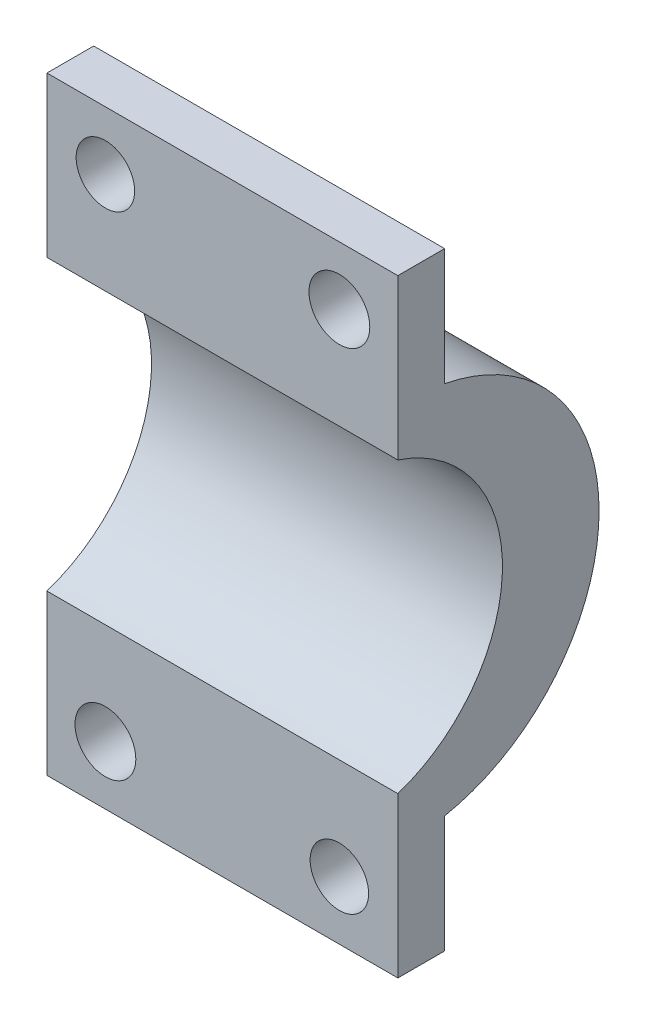
SolidWorks part; units mm, degrees
material "ABS"
ref_plane "Спереди" through (0, 0, 0) normal (0, 0, 1) x (1, 0, 0)
ref_plane "Сверху" through (0, 0, 0) normal (0, 1, 0) x (1, 0, 0)
ref_plane "Справа" through (0, 0, 0) normal (1, 0, 0) x (0, 0, -1)
sketch "Эскиз1" plane through (0, 0, 0) normal (0, 0, 1) x (1, 0, 0)
  line L0 (0, 0) -> (30, 0)
  line L1 (30, 0) -> (30, 32)
  line L2 (30, 32) -> (0, 32)
  line L3 (0, 32) -> (0, 0)
  dimension "D1" = 30
  dimension "D2" = 32
extrude "Бобышка-Вытянуть1" add sketch "Эскиз1" along normal blind 7
ref_plane "Плоскость5" through (0, 0, 0) normal (-1, 0, 0) x (0, 0, 1)
sketch "Эскиз2" plane through (0, 0, 0) normal (-1, 0, 0) x (0, 0, 1)
  line L0 (7, 32) -> (17.9408, 32)
  line L1 (17.9408, 0) -> (7, 0)
  line L2 (7, 0) -> (7, 32)
  line L3 (17.9408, 32) -> (17.9408, 28.35)
  line L4 (17.9408, 3.65) -> (17.9408, 0)
  arc A2 (17.9408, 28.35) -> (17.9408, 3.65) centre (22, 16) ccw
  dimension "D1" = 13
  dimension "D3" = 3.65
  dimension "D2" = 16
  dimension "D4" = 3.65
  dimension "D5" = 15
extrude "Бобышка-Вытянуть2" add sketch "Эскиз2" against normal blind 30
sketch "Эскиз3" plane through (0, 0, 17.9408) normal (0, 0, -1) x (-1, 0, 0)
  line L0 (-30, 16) -> (-30, -10)
  line L1 (-30, 0) -> (-30, 32) construction
  line L2 (-30, -10) -> (0, -10)
  line L3 (0, -10) -> (0, 42)
  line L4 (0, -13.695) -> (0, 13.695) construction
  line L5 (0, 42) -> (-30, 42)
  line L6 (-30, 42) -> (-30, 16)
  line L7 (-30, 37) -> (0, 37) construction
  line L8 (-30, -5) -> (0, -5) construction
  line L9 (-30, 32) -> (0, 32)
  line L10 (-30, 0) -> (0, 0)
  line L11 (0, 32) -> (0, 42)
  line L12 (-30, 42) -> (-30, 32)
  line L13 (-30, 0) -> (-30, -10)
  line L14 (0, -10) -> (0, 0)
  circle A0 centre (-25, 37) radius 2.6
  circle A1 centre (-5, 37) radius 2.5
  circle A2 centre (-5, -5) radius 2.6
  circle A3 centre (-25, -5) radius 2.5
  point P16 (-25, 37)
  point P17 (-5, 37)
  point P18 (-5, -5)
  point P19 (-25, -5)
  line M20 (-30, 32) -> (0, 32)
  dimension "D7" = 5.2
  dimension "D9" = 5
  dimension "D10" = 5
  dimension "D12" = 5.2
  dimension "D13" = 5
  dimension "D1" = 10
  dimension "D2" = 10
  dimension "D3" = 30
  dimension "D4" = 5
  dimension "D5" = 5
  dimension "D6" = 5
  dimension "D8" = 5
  dimension "D11" = 5
extrude "Бобышка-Вытянуть3" add sketch "Эскиз3" along normal blind 4 contours L6 L5 L3 A0 A1 M20 | L0 L10 L3 L2 A2 A3
sketch "Эскиз4" plane through (30, 0, 0) normal (1, 0, 0) x (0, 0, -1)
  line L0 (-13.9408, 32) -> (0, 32)
  line L1 (0, 32) -> (0, 0)
  line L2 (0, 0) -> (-13.9408, 0)
  arc A0 (-13.9408, 32) -> (-13.9408, 0) centre (-17.0334, 16) cw
  dimension "D1" = 16.2961
extrude "Вырез-Вытянуть1" cut sketch "Эскиз4" against normal blind 60
